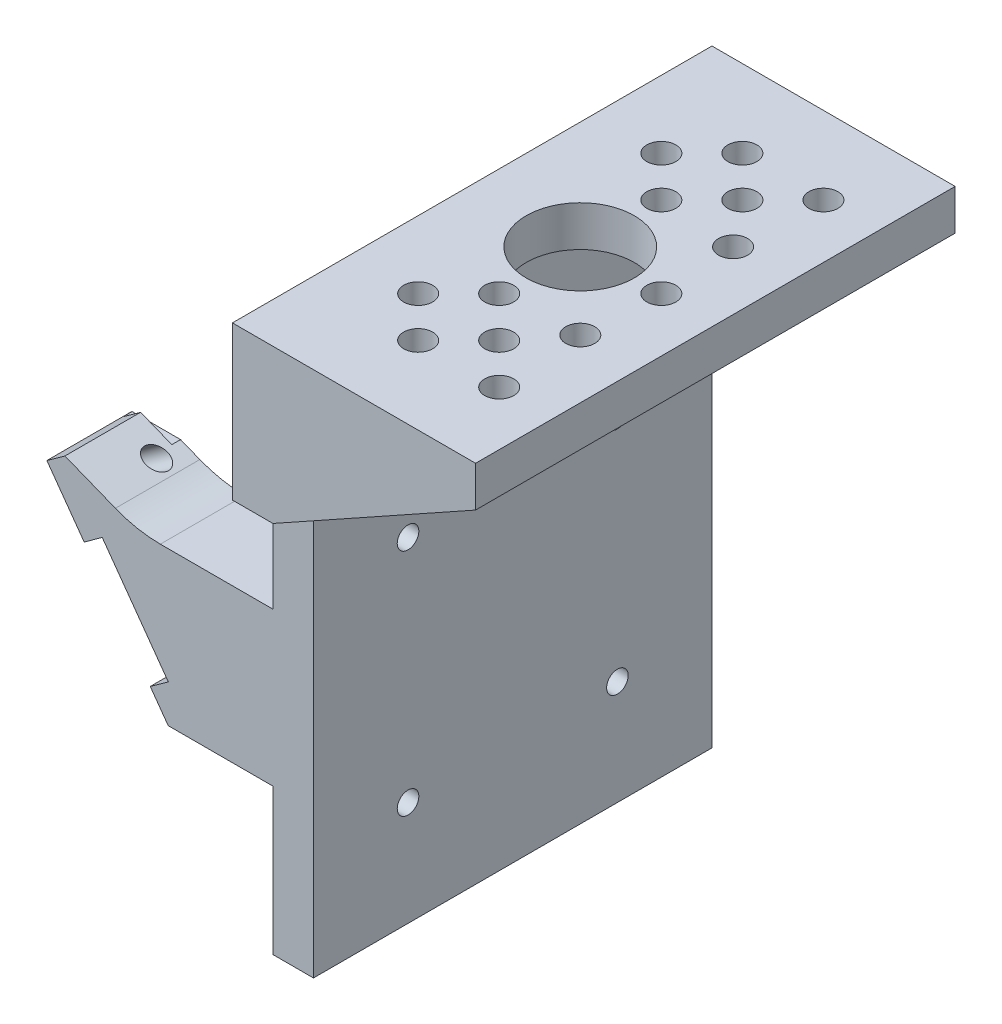
SolidWorks part; units mm, degrees
ref_plane "前视基准面" through (0, 0, 0) normal (0, 0, 1) x (1, 0, 0)
ref_plane "上视基准面" through (0, 0, 0) normal (0, 1, 0) x (1, 0, 0)
ref_plane "右视基准面" through (0, 0, 0) normal (1, 0, 0) x (0, 0, -1)
other "Configuration Table"
sketch "草图1" plane through (0, 0, 0) normal (0, 0, 1) x (1, 0, 0)
  line L0 (0, 0) -> (18, 0)
  line L2 (18, 0) -> (18, -3)
  line L4 (0, -42) -> (3, -42)
  line L8 (3, -11.36) -> (18, -3)
  line L9 (3, -11.36) -> (3, -42)
  line L10 (0, 0) -> (0, -42)
  dimension "D1" = 18
  dimension "D2" = 42
  dimension "D3" = 3
  dimension "D4" = 3
  dimension "D5" = 11.36
extrude "凸台-拉伸1" add sketch "草图1" along normal blind 35.5
ref_plane "基准面1" through (18, 0, 0) normal (1, 0, 0) x (0, 0, -1)
sketch "草图2" plane through (18, 0, 0) normal (1, 0, 0) x (0, 0, -1)
  line L0 (-32.5, -3) -> (-32.5, -42)
  line L3 (-17.75, -3) -> (-17.75, -39.7127) construction
  line L4 (-3, -3) -> (-3, -42)
  line L7 (-32.5, -3) -> (-3, -3)
  line L8 (-32.5, -42) -> (-3, -42)
  line L10 (-35.5, -3) -> (0, -3) construction
  line L11 (-35.5, -42) -> (0, -42) construction
  dimension "D1" = 29.5
extrude "切除-拉伸2" cut sketch "草图2" against normal blind 15
sketch "草图3" plane through (0, 0, 0) normal (1, 0, 0) x (0, 0, -1)
  line L0 (-32.5, -11.36) -> (-35.5, -11.36)
  line L1 (-35.5, -11.36) -> (-35.5, -42)
  line L5 (-32.5, -11.36) -> (-32.5, -42)
  line L6 (-35.5, -42) -> (0, -42) construction
  line L7 (-32.5, -42) -> (-35.5, -42)
  line L8 (-3, -11.36) -> (-3, -42)
  line L9 (-3, -42) -> (0, -42)
  line L10 (0, -42) -> (0, -11.36)
  line L11 (0, -42) -> (0, -11.36) construction
  line L12 (0, -11.36) -> (0, -3) construction
  line L13 (0, -11.36) -> (-3, -11.36)
extrude "切除-拉伸3" cut sketch "草图3" along normal blind 3
sketch "草图4" plane through (0, 0, 0) normal (1, 0, 0) x (0, 0, -1)
  line L0 (-17.75, -3) -> (-17.75, -44.0016) construction
  line L1 (-3, -3) -> (-32.5, -3) construction
  line L4 (-32.5, -42) -> (-3, -42) construction
  circle A0 centre (-10, -17.25) radius 0.8
  circle A1 centre (-10, -34.25) radius 0.8
  circle A2 centre (-25.5, -34.25) radius 0.8
  circle A3 centre (-25.5, -17.25) radius 0.8
  dimension "D2" = 1.6
  dimension "D3" = 1.6
  dimension "D1" = 7.75
  dimension "D4" = 17
  dimension "D5" = 15.5
extrude "切除-拉伸4" cut sketch "草图4" along normal blind 3
sketch "草图5" plane through (0, 0, 0) normal (0, 1, 0) x (1, 0, 0)
  line L0 (0, 0) -> (18, -35.5) construction
  line L1 (18, -19.525) -> (18, 19.525) construction
  line L2 (18, -35.5) -> (0, -35.5) construction
  line L3 (18, 0) -> (0, -35.5) construction
  line L4 (18, 0) -> (0, 0) construction
  line L5 (8, -2.6546) -> (8, -37.0916) construction
  line L6 (18.5676, -17.75) -> (-2.967, -17.75) construction
  circle A5 centre (14, -17.75) radius 1.075
  circle A27 centre (13.6569, -23.4069) radius 1.075
  circle A29 centre (14, -29.75) radius 1.075
  circle A32 centre (5, -26.75) radius 1.075
  circle A36 centre (5, -8.75) radius 1.075
  circle A38 centre (14, -5.75) radius 1.075
  circle A41 centre (13.6569, -12.0931) radius 1.075
  circle A44 centre (8, -17.75) radius 4
  circle A45 centre (8, -17.75) radius 6 construction
  circle A46 centre (8, -17.75) radius 8 construction
  circle A47 centre (8, -23.75) radius 1.075
  circle A48 centre (8, -11.75) radius 1.075
  circle A49 centre (11, -26.75) radius 1.075
  circle A50 centre (11, -8.75) radius 1.075
  circle A51 centre (8, -29.75) radius 1.075
  circle A52 centre (8, -5.75) radius 1.075
  point P71 (9, -17.75)
  dimension "D3" = 16
  dimension "D4" = 10
  dimension "D5" = 2.15
  dimension "D6" = 2.15
  dimension "D7" = 8
  dimension "D8" = 2.15
  dimension "D9" = 2.15
  dimension "D12" = 6
  dimension "D15" = 2.15
  dimension "D20" = 12
  dimension "D14" = 3
  dimension "D18" = 2.15
  dimension "D16" = 12
  dimension "D10" = 45
  dimension "D11" = 12
  dimension "D17" = 9
extrude "切除-拉伸6" cut sketch "草图5" against normal blind 4
sketch "Sketch1" plane through (0, 0, 0) normal (-1, 0, 0) x (0, 0, 1)
  line L0 (32.5, -42) -> (32.5, -11.36) construction
  line L1 (32.5, -42) -> (3, -42) construction
  line L2 (3, -11.36) -> (3, -42) construction
  circle A0 centre (30.25, -26) radius 2
  circle A1 centre (5.25, -26) radius 2
  dimension "D2" = 4
  dimension "D3" = 16
  dimension "D4" = 4
  dimension "D1" = 2.25
  dimension "D5" = 2.25
  dimension "D6" = 16
sketch "Sketch2" plane through (0, 0, 0) normal (-1, 0, 0) x (0, 0, 1)
  line L0 (35.5, 0) -> (0, 0) construction
  line L1 (3, -42) -> (32.5, -42)
  line L2 (3, -42) -> (3, 0)
  line L3 (3, 0) -> (32.5, 0)
  line L4 (32.5, -42) -> (32.5, 0)
  line L5 (32.5, -42) -> (32.5, -11.36) construction
extrude "Boss-Extrude1" add sketch "Sketch2" along normal blind 22
sketch "Sketch3" plane through (0, 0, 32.5) normal (0, 0, 1) x (1, 0, 0)
  line L0 (0, -42) -> (-22, -11.36)
  line L1 (-22, -42) -> (-22, 0) construction
  line L2 (-22, -11.36) -> (-22, -42)
  line L3 (-22, -42) -> (0, -42)
extrude "Cut-Extrude1" cut sketch "Sketch3" against normal through all
sketch "Sketch4" plane through (-22, 0, 0) normal (-1, 0, 0) x (0, 0, 1)
  line L0 (3, -42) -> (32.5, -42) construction
  line L1 (9.25, 0) -> (26.25, 0)
  line L2 (9.25, 0) -> (9.25, -42)
  line L3 (9.25, -42) -> (26.25, -42)
  line L4 (26.25, 0) -> (26.25, -42)
  line L5 (3, 0) -> (3, -11.36) construction
  line L6 (32.5, -11.36) -> (32.5, 0) construction
  dimension "D1" = 6.25
  dimension "D2" = 6.25
extrude "Cut-Extrude2" cut sketch "Sketch4" against normal blind 22
sketch "Sketch5" plane through (-19.8982, -14.2872, 0) normal (-0.8123, -0.5832, 0) x (0, 0, 1)
  line L0 (3, 3.6036) -> (3, -34.1165) construction
  line L1 (32.5, -34.1165) -> (32.5, 3.6036) construction
  circle A0 centre (7.25, -19.7194) radius 0.8
  circle A1 centre (28.25, -19.7194) radius 0.8
  circle A2 centre (7.25, -7.7194) radius 0.8
  circle A3 centre (28.25, -7.7194) radius 0.8
  dimension "D1" = 1.6
  dimension "D2" = 4.25
  dimension "D3" = 4.25
  dimension "D4" = 4.25
  dimension "D5" = 4.25
  dimension "D6" = 12
  dimension "D7" = 12
extrude "Cut-Extrude3" cut sketch "Sketch5" against normal blind 6 contours A2 | A0 | A3 | A1
sketch "Sketch6" plane through (0, 0, 32.5) normal (0, 0, 1) x (1, 0, 0)
  line L0 (-18.6403, -16.0392) -> (0, -2.6551)
  line L1 (0, -42) -> (-22, -11.36) construction
  line L2 (0, -11.36) -> (0, 0) construction
  line L3 (0, -2.6551) -> (0, 0)
  line L4 (0, 0) -> (-22, 0)
  line L5 (-22, 0) -> (-22, -11.36)
  line L6 (-22, -11.36) -> (-18.6403, -16.0392)
extrude "Cut-Extrude4" cut sketch "Sketch6" against normal through all both and the other way through all
sketch "Sketch7" plane through (0, 0, 32.5) normal (0, 0, 1) x (1, 0, 0)
  line L0 (-5.9226, -33.7515) -> (0, -33.7515)
  line L1 (0, -42) -> (-18.6403, -16.0392) construction
  line L2 (0, -33.7515) -> (0, -42)
  line L3 (0, -42) -> (-5.9226, -33.7515)
extrude "Cut-Extrude5" cut sketch "Sketch7" against normal through all both and the other way through all
sketch "Sketch8" plane through (0, 0, 32.5) normal (0, 0, 1) x (1, 0, 0)
  line L0 (-16.7355, -18.692) -> (-15.3975, -17.7313)
  line L1 (-5.9226, -33.7515) -> (-18.6403, -16.0392) construction
  line L2 (-15.3975, -17.7313) -> (-17.3023, -15.0785)
  line L3 (-18.6403, -16.0392) -> (0, -2.6551) construction
  line L4 (-17.3023, -15.0785) -> (-18.6403, -16.0392)
  line L5 (-18.6403, -16.0392) -> (-16.7355, -18.692)
  line L6 (-13.9743, -22.5375) -> (-12.6363, -21.5768)
  line L7 (-12.6363, -21.5768) -> (-8.7981, -26.9224)
  line L8 (-8.7981, -26.9224) -> (-10.1361, -27.8831)
  line L9 (-10.1361, -27.8831) -> (-13.9743, -22.5375)
  line L10 (-7.0891, -32.1269) -> (-5.7981, -31.2)
  line L11 (-3.9661, -33.7515) -> (-5.9226, -33.7515)
  line L12 (0, -33.7515) -> (-5.9226, -33.7515) construction
  line L13 (-5.9226, -33.7515) -> (-7.0891, -32.1269)
  line L14 (-5.7981, -31.2) -> (-3.9661, -33.7515)
  dimension "D1" = 2
  dimension "D2" = 8
extrude "Cut-Extrude6" cut sketch "Sketch8" against normal through all both and the other way through all
sketch "Sketch9" plane through (0, 0, 32.5) normal (0, 0, 1) x (1, 0, 0)
  line L0 (-7.0891, -32.1269) -> (0, -32.1269)
  line L1 (0, -32.1269) -> (0, -33.7515)
  line L2 (0, -33.7515) -> (-7.0891, -33.7515)
  line L3 (-7.0891, -33.7515) -> (-7.0891, -32.1269)
extrude "Cut-Extrude7" cut sketch "Sketch9" against normal through all both and the other way through all
sketch "Sketch10" plane through (0, 0, 9.25) normal (0, 0, 1) x (1, 0, 0)
  line L1 (0, -2.6551) -> (0, -16.9716) construction
  line L3 (-10.0599, -19.854) -> (0, -19.854)
  line L4 (0, -17.5284) -> (0, -32.1269) construction
  line L5 (0, -19.854) -> (0, -13.9576)
  line L6 (-10.0599, -19.854) -> (-15.3975, -17.7313)
  line L7 (-15.3975, -17.7313) -> (-17.3023, -15.0785)
  line L8 (-17.3023, -15.0785) -> (0, -2.6551)
  line L9 (0, -2.6551) -> (-17.3023, -15.0785) construction
  line L10 (0, -2.6551) -> (0, -13.9576)
extrude "Cut-Extrude8" cut sketch "Sketch10" against normal through all both and the other way through all
sketch "Sketch11" plane through (0, 0, 0) normal (-1, 0, 0) x (0, 0, 1)
  line L1 (8.6, -15.85) -> (11.4, -15.85)
  line L2 (8.6, -15.85) -> (8.6, -18.65)
  line L3 (8.6, -18.65) -> (11.4, -18.65)
  line L4 (11.4, -15.85) -> (11.4, -18.65)
  line L5 (8.6, -15.85) -> (11.4, -18.65) construction
  line L6 (8.6, -18.65) -> (11.4, -15.85) construction
  line L7 (24.1, -15.85) -> (26.9, -15.85)
  line L8 (24.1, -15.85) -> (24.1, -18.65)
  line L9 (24.1, -18.65) -> (26.9, -18.65)
  line L10 (26.9, -15.85) -> (26.9, -18.65)
  line L11 (24.1, -15.85) -> (26.9, -18.65) construction
  line L12 (24.1, -18.65) -> (26.9, -15.85) construction
  point P0 (10, -17.25)
  point P6 (25.5, -17.25)
  dimension "D1" = 2.8
  dimension "D2" = 2.8
  dimension "D3" = 2.8
  dimension "D4" = 2.8
extrude "Cut-Extrude9" cut sketch "Sketch11" along normal through all
sketch "Sketch12" plane through (0, 0, 32.5) normal (0, 0, 1) x (1, 0, 0)
  line L0 (-5.7981, -31.2) -> (0, -31.2)
  line L1 (0, -31.2) -> (0, -32.1269)
  line L2 (0, -32.1269) -> (-5.1326, -32.1269) construction
  line L3 (0, -32.1269) -> (-9.1634, -32.1269)
  line L5 (-9.1634, -32.1269) -> (-9.1634, -31.2)
  line L6 (-9.1634, -31.2) -> (-5.7981, -31.2)
extrude "Cut-Extrude10" cut sketch "Sketch12" against normal through all contours L0 L1 L3 L5 L6
sketch "Sketch13" plane through (-19.8982, -14.2872, 0) normal (-0.8123, -0.5832, 0) x (0, 0, 1)
  line L0 (3, -16.7376) -> (9.25, -16.7376)
  line L1 (3, -16.7376) -> (3, -18.5424)
  line L2 (3, -16.7376) -> (3, -20.8209) construction
  line L3 (3, -18.5424) -> (9.25, -18.5424)
  line L4 (9.25, -20.8209) -> (9.25, -16.7376) construction
  line L5 (9.25, -18.5424) -> (9.25, -16.7376)
  line L6 (26.25, -16.7376) -> (32.5, -16.7376)
  line L7 (26.25, -16.7376) -> (32.5, -16.7376) construction
  line L8 (26.25, -16.7376) -> (26.25, -20.8209) construction
  line L9 (32.5, -16.7376) -> (32.5, -18.5424)
  line L10 (32.5, -20.8209) -> (32.5, -16.7376) construction
  line L11 (32.5, -18.5424) -> (26.25, -18.5424)
  line L12 (26.25, -18.5424) -> (26.25, -16.7376)
extrude "Cut-Extrude11" cut sketch "Sketch13" against normal up to surface (1.6472 mm away) up to face at (-10.7172, -24.2496, 29.375)
fillet "Fillet1" radius 10 1 edges at (-10.0599, -19.854, 6.125)
fillet "Fillet2" radius 9 1 edges at (-10.0599, -19.854, 29.375)
